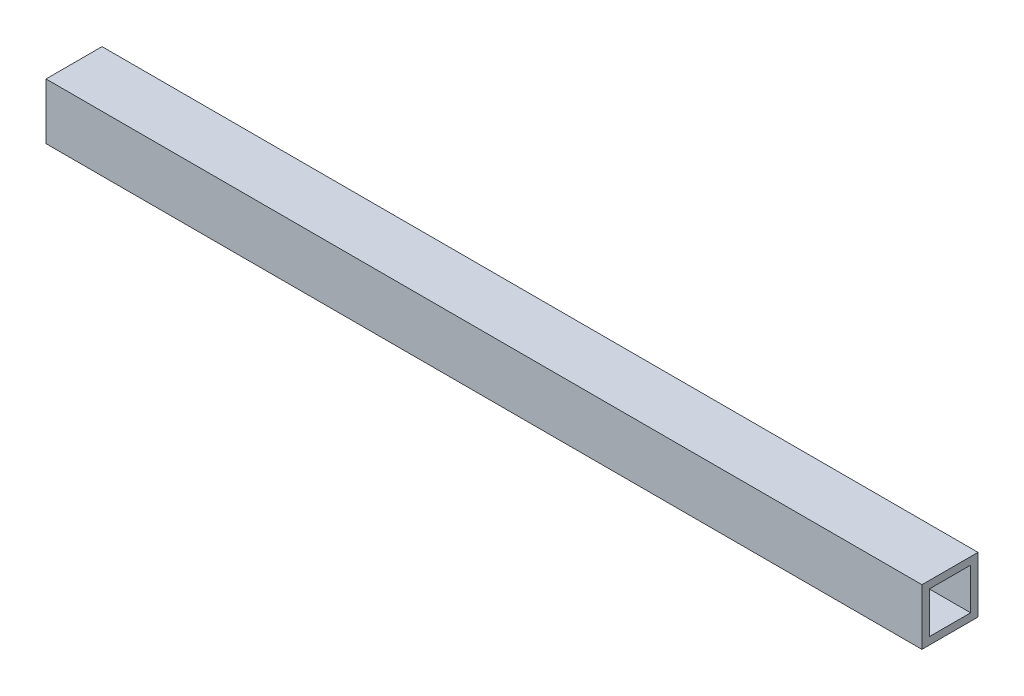
SolidWorks part; units mm, degrees
ref_plane "Front Plane" through (0, 0, 0) normal (0, 0, 1) x (1, 0, 0)
ref_plane "Top Plane" through (0, 0, 0) normal (0, 1, 0) x (1, 0, 0)
ref_plane "Right Plane" through (0, 0, 0) normal (1, 0, 0) x (0, 0, -1)
sketch "Sketch1" plane through (0, 0, 0) normal (1, 0, 0) x (0, 0, -1)
  line L0 (5, 5) -> (5, 33)
  line L1 (0, 0) -> (38, 0)
  line L2 (0, 0) -> (0, 38)
  line L3 (0, 38) -> (38, 38)
  line L4 (38, 0) -> (38, 38)
  line L5 (5, 33) -> (33, 33)
  line L6 (33, 5) -> (33, 33)
  line L7 (5, 5) -> (33, 5)
  dimension "D1" = 38
  dimension "D2" = 38
  dimension "D3" = 5
extrude "Boss-Extrude1" add sketch "Sketch1" along normal blind 594
